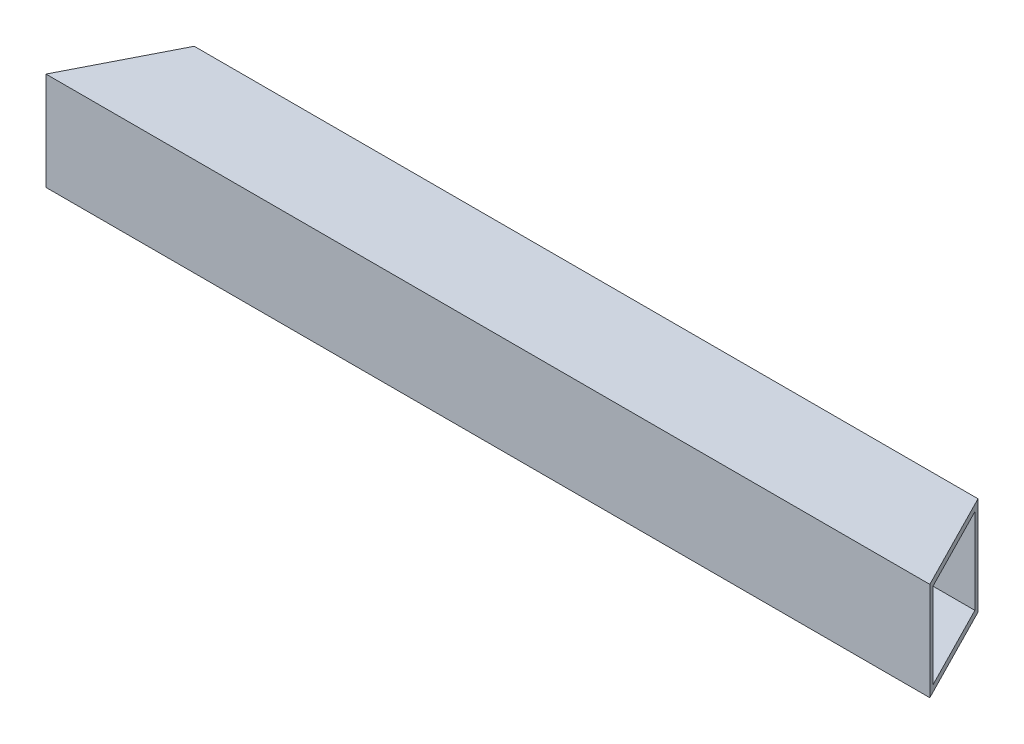
SolidWorks part; units mm, degrees
material "6061 Alloy"
ref_plane "Front Plane" through (0, 0, 0) normal (0, 0, 1) x (1, 0, 0)
ref_plane "Top Plane" through (0, 0, 0) normal (0, 1, 0) x (1, 0, 0)
ref_plane "Right Plane" through (0, 0, 0) normal (1, 0, 0) x (0, 0, -1)
sketch "Sketch1" plane through (0, 0, 0) normal (1, 0, 0) x (0, 0, -1)
  line L1 (12.7, -12.7) -> (-12.7, -12.7)
  line L2 (12.7, -12.7) -> (12.7, 12.7)
  line L3 (12.7, 12.7) -> (-12.7, 12.7)
  line L4 (-12.7, -12.7) -> (-12.7, 12.7)
  line L5 (12.7, -12.7) -> (-12.7, 12.7) construction
  line L6 (12.7, 12.7) -> (-12.7, -12.7) construction
  point P0 (0, 0)
  dimension "D1" = 25.4
  dimension "D2" = 25.4
extrude "Boss-Extrude1" add sketch "Sketch1" along normal mid plane 228.6 contours L2 L1 L4 L3
sketch "Sketch2" plane through (0, 12.7, 0) normal (0, 1, 0) x (1, 0, 0)
  line L0 (114.3, -12.7) -> (101.3581, 12.7)
  line L1 (114.3, 12.7) -> (-114.3, 12.7) construction
  line L2 (114.3, 12.7) -> (114.3, -12.7) construction
  line L3 (101.3581, 12.7) -> (114.3, 12.7)
  line L4 (114.3, 12.7) -> (114.3, -12.7)
  dimension "D1" = 27
extrude "Cut-Extrude1" cut sketch "Sketch2" against normal blind 685.8
sketch "Sketch5" plane through (-114.3, 0, 0) normal (-1, 0, 0) x (0, 0, 1)
  line L0 (-12.7, 12.7) -> (12.7, 12.7) construction
  line L1 (-11.049, -11.049) -> (11.049, -11.049)
  line L2 (-11.049, -11.049) -> (-11.049, 11.049)
  line L3 (-11.049, 11.049) -> (11.049, 11.049)
  line L4 (11.049, -11.049) -> (11.049, 11.049)
  line L5 (-11.049, -11.049) -> (11.049, 11.049) construction
  line L6 (-11.049, 11.049) -> (11.049, -11.049) construction
  line L7 (12.7, -12.7) -> (12.7, 12.7) construction
  point P0 (0, 0)
  dimension "D1" = 1.651
  dimension "D2" = 1.651
extrude "Cut-Extrude3" cut sketch "Sketch5" against normal through all contours L2 L1 L4 L3
sketch "Sketch6" plane through (0, 12.7, 0) normal (0, 1, 0) x (1, 0, 0)
  line L0 (-114.3, -12.7) -> (-101.3581, 12.7)
  line L1 (101.3581, 12.7) -> (-114.3, 12.7) construction
  line L2 (-114.3, 12.7) -> (-114.3, -12.7) construction
  line L3 (-101.3581, 12.7) -> (-114.3, 12.7)
  line L4 (-114.3, 12.7) -> (-114.3, -12.7)
  dimension "D1" = 27
extrude "Cut-Extrude4" cut sketch "Sketch6" against normal blind 685.8
